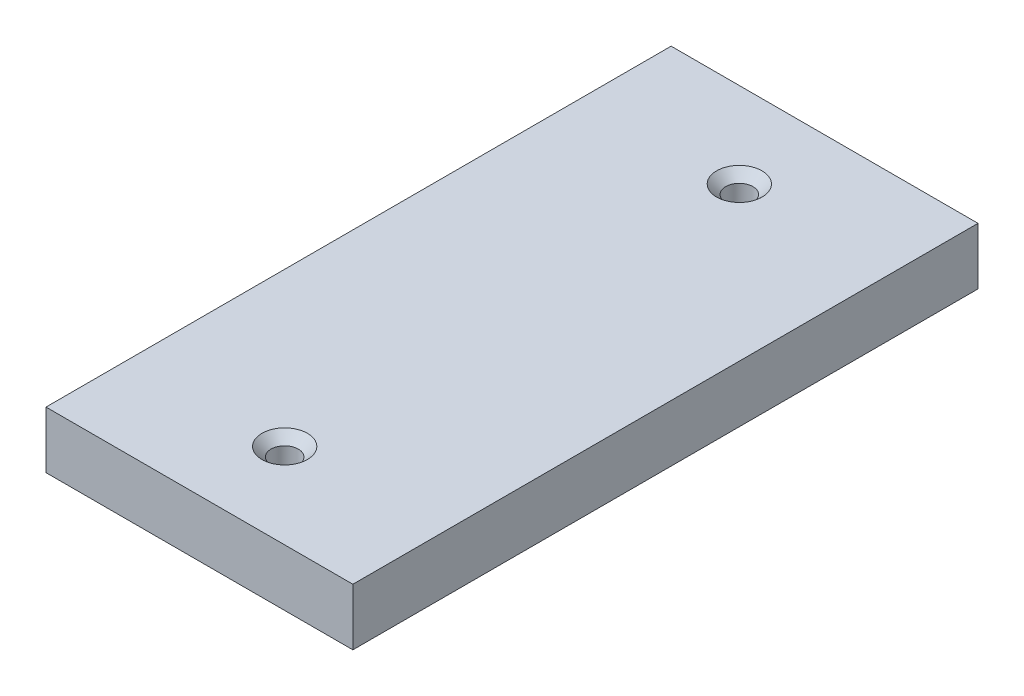
SolidWorks part; units mm, degrees
material "Сталь 08пс ГОСТ 535-88"
ref_plane "Спереди" through (0, 0, 0) normal (0, 0, 1) x (1, 0, 0)
ref_plane "Сверху" through (0, 0, 0) normal (0, 1, 0) x (1, 0, 0)
ref_plane "Справа" through (0, 0, 0) normal (1, 0, 0) x (0, 0, -1)
sketch "Эскиз1" plane through (0, 0, 0) normal (0, 0, 1) x (1, 0, 0)
  line L0 (-34.4035, 28.782) -> (34.4035, -28.782) construction
  line L1 (-34.4035, 28.782) -> (34.4035, 28.782)
  line L2 (-34.4035, 28.782) -> (-34.4035, -28.782)
  line L3 (-34.4035, -28.782) -> (34.4035, -28.782)
  line L4 (34.4035, 28.782) -> (34.4035, -28.782)
sketch "Эскиз2" plane through (0, 0, 0) normal (0, 1, 0) x (1, 0, 0)
  line L1 (-27, -55) -> (27, -55)
  line L2 (-27, -55) -> (-27, 55)
  line L3 (-27, 55) -> (27, 55)
  line L4 (27, -55) -> (27, 55)
  line L5 (-27, -55) -> (27, 55) construction
  line L6 (-27, 55) -> (27, -55) construction
  point P0 (0, 0)
  dimension "D1" = 110
  dimension "D2" = 54
extrude "Бобышка-Вытянуть1" add sketch "Эскиз2" along normal mid plane 10
sketch "Эскиз3" plane through (0, 5, 0) normal (0, 1, 0) x (1, 0, 0)
  line L0 (0, 26.6908) -> (0, -21.4129) construction
  line L1 (-8.3691, 0) -> (10.7819, 0) construction
  circle A0 centre (0, 40) radius 2.4
  circle A1 centre (0, -40) radius 2.4
  dimension "D1" = 4.8
  dimension "D2" = 80
extrude "Вырез-Вытянуть1" cut sketch "Эскиз3" against normal up to next
chamfer "Фаска1" distance 1.6 angle 45 2 edges at (0, 5, 42.4) (0, 5, -37.6)
